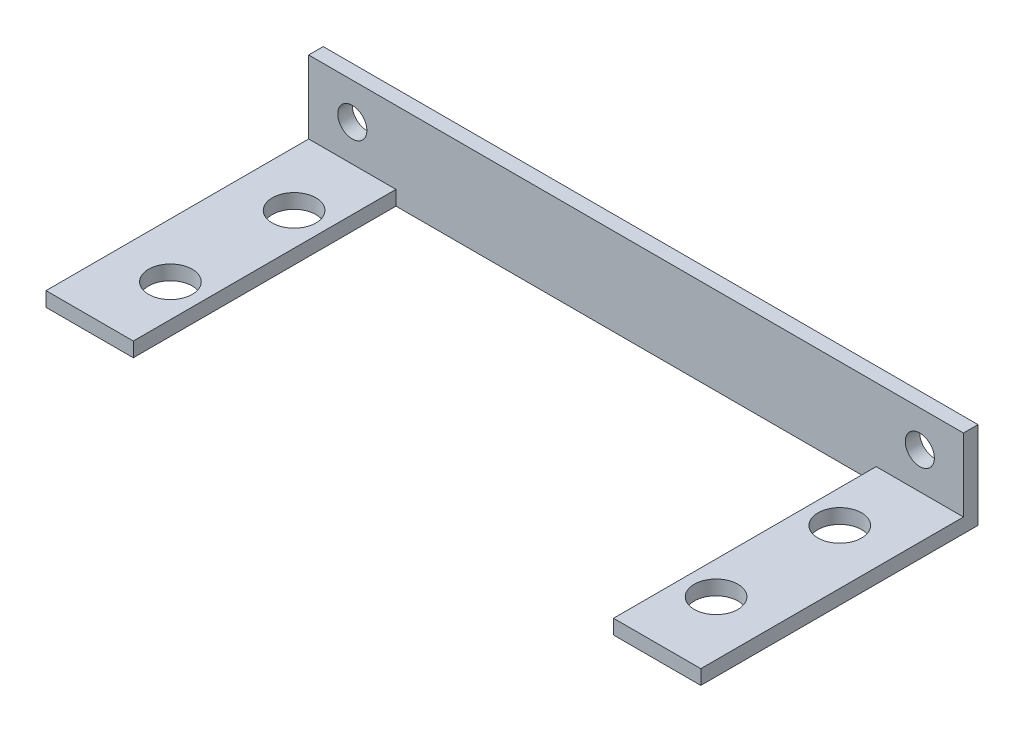
SolidWorks part; units mm, degrees
ref_plane "Front Plane" through (0, 0, 0) normal (0, 0, 1) x (1, 0, 0)
ref_plane "Top Plane" through (0, 0, 0) normal (0, 1, 0) x (1, 0, 0)
ref_plane "Right Plane" through (0, 0, 0) normal (1, 0, 0) x (0, 0, -1)
sketch "Sketch1" plane through (0, 0, 0) normal (1, 0, 0) x (0, 0, -1)
  line L0 (-38.1, 0) -> (0, 0)
  line L1 (0, 0) -> (0, 12)
  line L2 (0, 12) -> (-2, 12)
  line L3 (-2, 12) -> (-2, 2)
  line L4 (-2, 2) -> (-38.1, 2)
  line L10 (-38.1, 0) -> (-38.1, 2)
  dimension "D1" = 2
  dimension "D2" = 12
  dimension "D3" = 38.1
  dimension "D4" = 2
extrude "Boss-Extrude1" add sketch "Sketch1" along normal mid plane 90
sketch "Sketch2" plane through (0, 2, 0) normal (0, 1, 0) x (1, 0, 0)
  line L1 (-33, -50.8) -> (33, -50.8)
  line L2 (-33, -50.8) -> (-33, -2)
  line L3 (-33, -2) -> (33, -2)
  line L4 (33, -50.8) -> (33, -2)
  line L5 (45, -2) -> (-45, -2) construction
  line L6 (0, -1030.5) -> (0, 48969.5) construction
  line L7 (-1021.4, -20) -> (48978.6, -20) construction
  circle A0 centre (37.5, -11.5) radius 3
  circle A1 centre (37.5, -28.5) radius 3
  circle A2 centre (-37.5, -11.5) radius 3
  circle A3 centre (-37.5, -28.5) radius 3
  point P6 (0, -2)
  point P14 (0, -50.8)
  dimension "D2" = 6
  dimension "D3" = 17
  dimension "D1" = 66
  dimension "D4" = 37.5
  dimension "D5" = 18
extrude "Cut-Extrude1" cut sketch "Sketch2" against normal through all
sketch "Sketch3" plane through (0, 0, 2) normal (0, 0, 1) x (1, 0, 0)
  line L0 (-39, 2) -> (-39, 12) construction
  line L2 (45, 12) -> (-45, 12) construction
  line L3 (0, 0) -> (0, 12) construction
  line L4 (-45, 12) -> (-45, 2) construction
  circle A0 centre (-39, 7) radius 2
  circle A1 centre (39, 7) radius 2
  dimension "D1" = 4
  dimension "D2" = 6
  dimension "D3" = 5
extrude "Cut-Extrude2" cut sketch "Sketch3" against normal through all both and the other way through all
